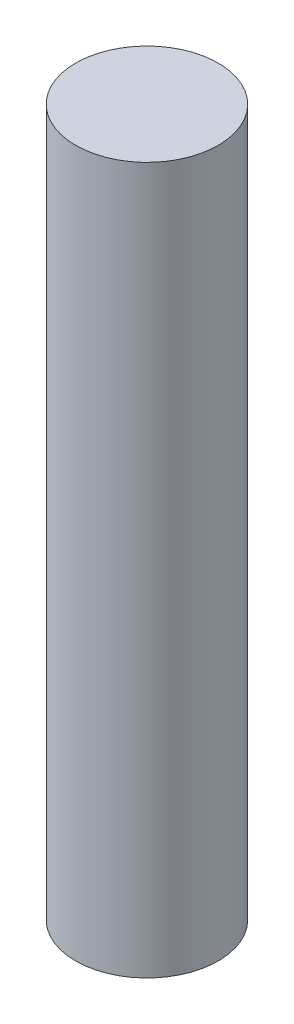
SolidWorks part; units mm, degrees
ref_plane "前视基准面" through (0, 0, 0) normal (0, 0, 1) x (1, 0, 0)
ref_plane "上视基准面" through (0, 0, 0) normal (0, 1, 0) x (1, 0, 0)
ref_plane "右视基准面" through (0, 0, 0) normal (1, 0, 0) x (0, 0, -1)
sketch "草图1" plane through (0, 0, 0) normal (0, 1, 0) x (1, 0, 0)
  circle A0 centre (-47.0612, 20.666) radius 4.5
extrude "凸台-拉伸1" add sketch "草图1" along normal blind 44.6
